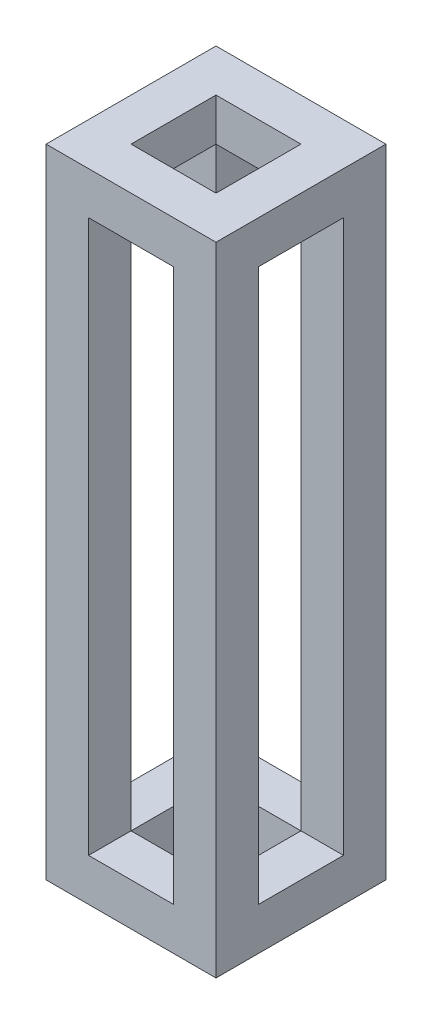
SolidWorks part; units mm, degrees
ref_plane "Front Plane" through (0, 0, 0) normal (0, 0, 1) x (1, 0, 0)
ref_plane "Top Plane" through (0, 0, 0) normal (0, 1, 0) x (1, 0, 0)
ref_plane "Right Plane" through (0, 0, 0) normal (1, 0, 0) x (0, 0, -1)
sketch "Sketch1" plane through (0, 0, 0) normal (0, 1, 0) x (1, 0, 0)
  line L1 (-40, 40) -> (40, 40)
  line L2 (-40, 40) -> (-40, -40)
  line L3 (-40, -40) -> (40, -40)
  line L4 (40, 40) -> (40, -40)
  line L5 (-40, 40) -> (40, -40) construction
  line L6 (-40, -40) -> (40, 40) construction
  line L7 (-20, 20) -> (20, 20)
  line L8 (-20, 20) -> (-20, -20)
  line L9 (-20, -20) -> (20, -20)
  line L10 (20, 20) -> (20, -20)
  line L11 (-20, 20) -> (20, -20) construction
  line L12 (-20, -20) -> (20, 20) construction
  point P0 (0, 0)
  point P6 (0, 0)
  dimension "D1" = 80
  dimension "D2" = 80
  dimension "D3" = 40
  dimension "D4" = 40
extrude "Boss-Extrude1" add sketch "Sketch1" along normal blind 20
ref_plane "Plane1" through (0, 300, 0) normal (0, 1, 0) x (1, 0, 0)
sketch "Sketch2" plane through (0, 300, 0) normal (0, 1, 0) x (1, 0, 0)
  line L1 (-40, 40) -> (-20, 40)
  line L2 (-40, 40) -> (-40, 20)
  line L3 (-40, 20) -> (-20, 20)
  line L4 (-20, 40) -> (-20, 20)
  line L5 (20, 20) -> (40, 20)
  line L6 (20, 20) -> (20, 40)
  line L7 (20, 40) -> (40, 40)
  line L8 (40, 20) -> (40, 40)
  line L9 (20, -20) -> (40, -20)
  line L10 (20, -20) -> (20, -40)
  line L11 (20, -40) -> (40, -40)
  line L12 (40, -20) -> (40, -40)
  line L13 (-20, -20) -> (-40, -20)
  line L14 (-20, -20) -> (-20, -40)
  line L15 (-20, -40) -> (-40, -40)
  line L16 (-40, -20) -> (-40, -40)
extrude "Boss-Extrude2" add sketch "Sketch2" against normal blind 300
sketch "Sketch4" plane through (0, 300, 0) normal (0, 1, 0) x (1, 0, 0)
  line L1 (-40, 40) -> (40, 40)
  line L2 (-40, 40) -> (-40, -40)
  line L3 (-40, -40) -> (40, -40)
  line L4 (40, 40) -> (40, -40)
  line L5 (-40, 40) -> (40, -40) construction
  line L6 (-40, -40) -> (40, 40) construction
  line L7 (-20, 20) -> (20, 20)
  line L8 (-20, 20) -> (-20, -20)
  line L9 (-20, -20) -> (20, -20)
  line L10 (20, 20) -> (20, -20)
  line L11 (-20, 20) -> (20, -20) construction
  line L12 (-20, -20) -> (20, 20) construction
  point P0 (0, 0)
  point P7 (0, 0)
extrude "Boss-Extrude3" add sketch "Sketch4" against normal blind 20
